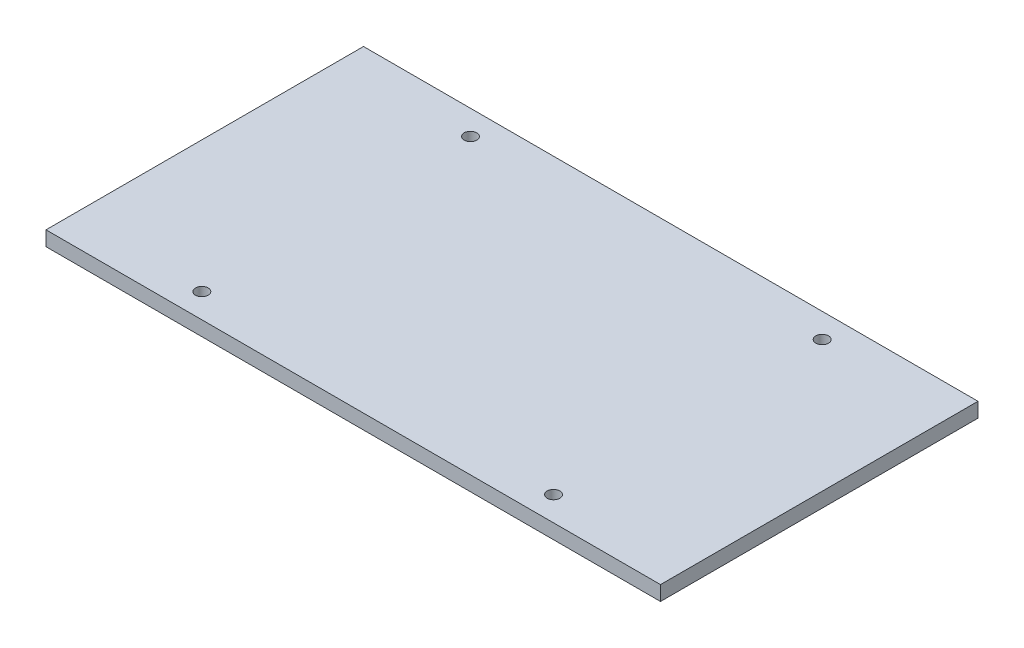
SolidWorks part; units mm, degrees
ref_plane "正面" through (0, 0, 0) normal (0, 0, 1) x (1, 0, 0)
ref_plane "平面" through (0, 0, 0) normal (0, 1, 0) x (1, 0, 0)
ref_plane "右側面" through (0, 0, 0) normal (1, 0, 0) x (0, 0, -1)
sketch "ｽｹｯﾁ1" plane through (0, 0, 0) normal (0, 1, 0) x (1, 0, 0)
  line L1 (0, 0) -> (125.8, 0)
  line L2 (0, 0) -> (0, 65)
  line L3 (0, 65) -> (125.8, 65)
  line L4 (125.8, 0) -> (125.8, 65)
  circle A0 centre (26.9, 60) radius 1.3
  circle A1 centre (98.9, 60) radius 1.3
  circle A2 centre (98.9, 5) radius 1.3
  circle A3 centre (26.9, 5) radius 1.3
  point P13 (121.3828, 63.3889)
  point P14 (8.7231, 2.0963)
  point P15 (4.762, 50.6767)
  point P16 (82.6934, 51.8742)
  point P17 (0, 0)
  point P18 (0, 0)
  point P19 (0, 0)
  point P20 (0, 0)
  point P21 (2.7354, 4.1573)
  dimension "D1" = 2.6
  dimension "D2" = 55
  dimension "D3" = 72
  dimension "D4" = 125.8
  dimension "D5" = 26.9
  dimension "D6" = 5
  dimension "D7" = 5
extrude "ﾎﾞｽ - 押し出し1" add sketch "ｽｹｯﾁ1" along normal blind 3
